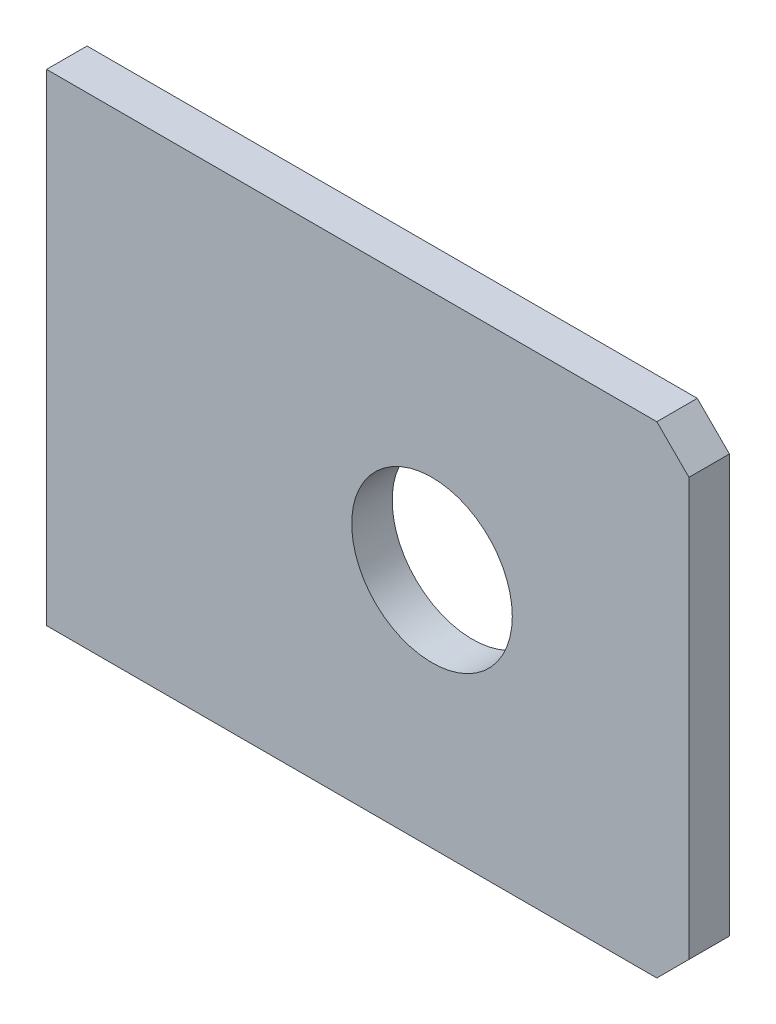
SolidWorks part; units mm, degrees
ref_plane "Plano frontal" through (0, 0, 0) normal (0, 0, 1) x (1, 0, 0)
ref_plane "Plano superior" through (0, 0, 0) normal (0, 1, 0) x (1, 0, 0)
ref_plane "Plano direito" through (0, 0, 0) normal (1, 0, 0) x (0, 0, -1)
sketch "Esboço1" plane through (0, 0, 0) normal (0, 0, 1) x (1, 0, 0)
  line L12 (14, -6.5) -> (14, 6.5)
  line L13 (14, 6.5) -> (13, 7.5)
  line L14 (13, 7.5) -> (-6, 7.5)
  line L15 (-6, 7.5) -> (-6, -7.5)
  line L16 (-6, -7.5) -> (13, -7.5)
  line L17 (13, -7.5) -> (14, -6.5)
  circle A1 centre (6, 0) radius 2.5
extrude "Ressalto-extrusão1" add sketch "Esboço1" along normal blind 1.26
